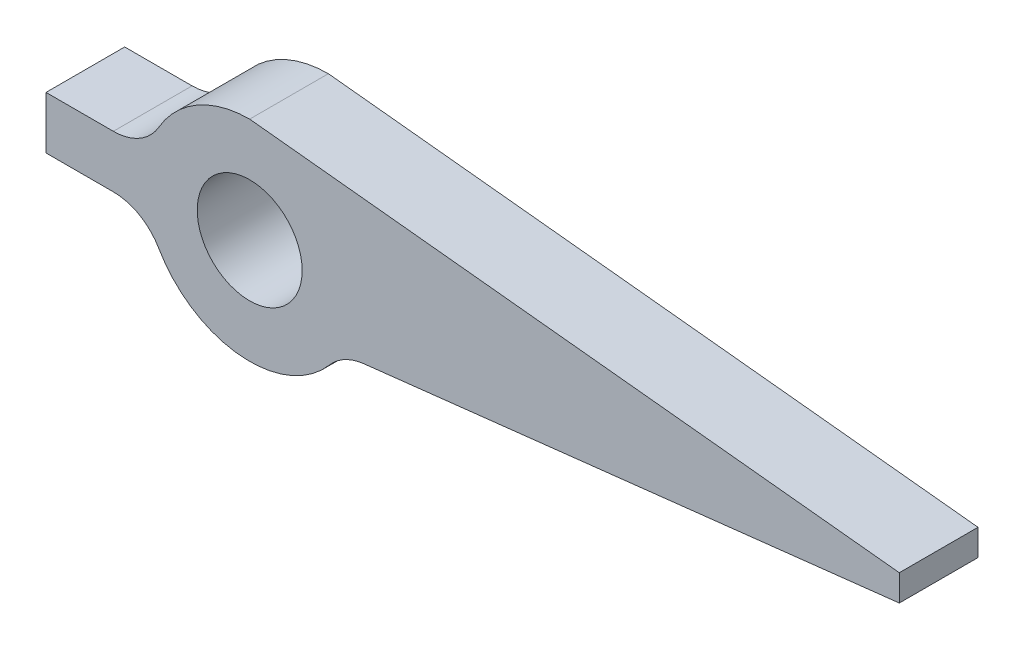
SolidWorks part; units mm, degrees
ref_plane "Front Plane" through (0, 0, 0) normal (0, 0, 1) x (1, 0, 0)
ref_plane "Top Plane" through (0, 0, 0) normal (0, 1, 0) x (1, 0, 0)
ref_plane "Right Plane" through (0, 0, 0) normal (1, 0, 0) x (0, 0, -1)
sketch "Sketch1" plane through (0, 0, 0) normal (0, 0, 1) x (1, 0, 0)
  line L6 (1.1663, 17.3543) -> (1.1663, 16.8537)
  line L11 (-10.8444, 15.7221) -> (-11.2161, 15.6505)
  line L12 (-11.2161, 18.6505) -> (1.1663, 17.3543)
  line L13 (-15.0981, 16.6505) -> (-15.0981, 17.1505)
  line L14 (-15.0981, 17.1505) -> (-13.1525, 17.1505)
  line L15 (-15.0981, 16.6505) -> (-15.0981, 16.1505)
  line L16 (-15.0981, 16.1505) -> (-13.1525, 16.1505)
  line L17 (-11.2161, 16.6505) -> (-11.2161, 16.1505)
  line L18 (-9.484, 15.6505) -> (1.1663, 16.8537)
  circle A2 centre (-11.2161, 16.6505) radius 1
  circle A3 centre (-11.2161, 16.6505) radius 2
extrude "Boss-Extrude1" add sketch "Sketch1" along normal blind 1.5
fillet "Fillet1" radius 1 1 edges at (-13.1525, 16.1505, 0.75)
fillet "Fillet2" radius 1 1 edges at (-13.1525, 17.1505, 0.75)
fillet "Fillet3" radius 1 1 edges at (-9.484, 15.6505, 0.75)
